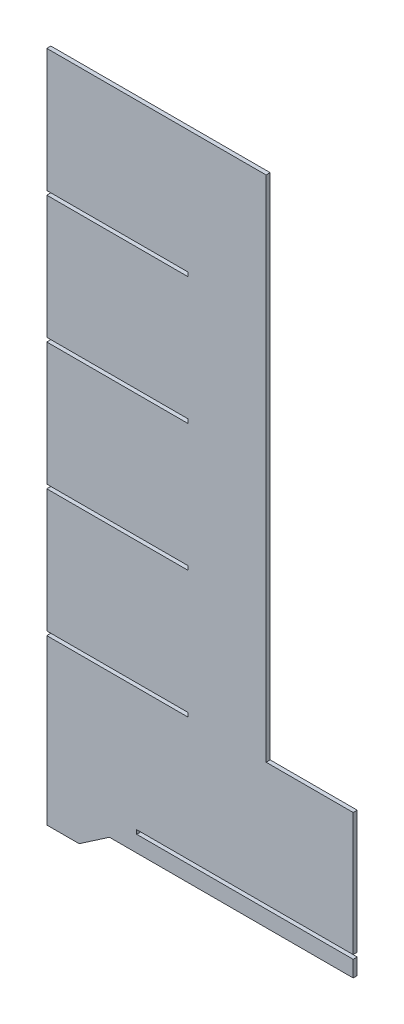
SolidWorks part; units mm, degrees
material "6061-T6 (SS)"
ref_plane "X-Y Datum" through (0, 0, 0) normal (0, 0, 1) x (1, 0, 0)
ref_plane "X-Z Datum" through (0, 0, 0) normal (0, 1, 0) x (1, 0, 0)
ref_plane "Y-Z Datum" through (0, 0, 0) normal (1, 0, 0) x (0, 0, -1)
sketch "Sketch1" plane through (0, 0, 0) normal (0, 0, 1) x (1, 0, 0)
  line L1 (129.0131, 254.2454) -> (-18.6854, 254.2454)
  line L3 (129.0131, -241.3467) -> (-18.6854, -241.3467)
  line L4 (-18.6854, 254.2454) -> (-18.6854, 157.667)
  line L24 (129.0131, 254.2454) -> (129.0131, -241.3467)
  line L25 (92.0885, 157.667) -> (-18.6854, 157.667)
  line L27 (92.0885, 154.492) -> (-18.6854, 154.492)
  line L29 (92.0885, 57.9136) -> (-18.6854, 57.9136)
  line L31 (92.0885, 54.7386) -> (-18.6854, 54.7386)
  line L33 (92.0885, -41.8399) -> (-18.6854, -41.8399)
  line L35 (92.0885, -45.0149) -> (-18.6854, -45.0149)
  line L37 (92.0885, -141.5933) -> (-18.6854, -141.5933)
  line L39 (92.0885, -144.7683) -> (-18.6854, -144.7683)
  line L41 (92.0885, -141.5933) -> (92.0885, -144.7683)
  line L42 (92.0885, -41.8399) -> (92.0885, -45.0149)
  line L43 (92.0885, 57.9136) -> (92.0885, 54.7386)
  line L44 (-18.6854, -144.7683) -> (-18.6854, -241.3467)
  line L45 (-18.6854, -45.0149) -> (-18.6854, -141.5933)
  line L46 (-18.6854, 54.7386) -> (-18.6854, -41.8399)
  line L47 (-18.6854, 154.492) -> (-18.6854, 57.9136)
  line L48 (92.0885, 157.667) -> (92.0885, 154.492)
extrude "Boss-Extrude2" add sketch "Sketch1" along normal blind 3.175
sketch "Sketch4" plane through (0, 0, 3.175) normal (0, 0, 1) x (1, 0, 0)
  line L1 (129.0131, 254.2454) -> (153.4072, 254.2454)
  line L2 (129.0131, 254.2454) -> (129.0131, -241.3467)
  line L3 (129.0131, -241.3467) -> (153.4072, -241.3467)
  line L4 (153.4072, 254.2454) -> (153.4072, -241.3467)
extrude "Boss-Extrude3" add sketch "Sketch4" against normal through all
sketch "Sketch6" plane through (0, 0, 3.175) normal (0, 0, 1) x (1, 0, 0)
  line L0 (-18.6854, -241.3467) -> (-18.6854, -355.6467)
  line L1 (-18.6854, -355.6467) -> (32.1146, -355.6467)
  line L3 (153.4072, -241.3467) -> (-18.6854, -241.3467)
  line L4 (153.4072, -241.3467) -> (153.4072, -292.1467)
  line L5 (153.4072, -292.1467) -> (32.1146, -355.6467)
extrude "Boss-Extrude5" [suppressed] add sketch "Sketch6" against normal through all
sketch "Sketch7" plane through (0, 0, 3.175) normal (0, 0, 1) x (1, 0, 0)
  line L0 (51.8072, -241.3467) -> (-18.6854, -241.3467)
  line L1 (51.8072, -244.5217) -> (51.8072, -241.3467)
  line L2 (153.4072, -244.5217) -> (51.8072, -244.5217)
  line L3 (153.4072, -244.5217) -> (153.4072, -257.2217)
  line L4 (153.4072, -257.2217) -> (30.4963, -257.2217)
  line L5 (30.4963, -257.2217) -> (6.7146, -273.4777)
  line L6 (-18.6854, -273.4777) -> (6.7146, -273.4777)
  line L7 (-18.6854, -241.3467) -> (-18.6854, -273.4777)
  point P0 (-51.634, -260.9767)
  point P9 (-18.6854, -241.3467)
extrude "Boss-Extrude6" add sketch "Sketch7" against normal through all
sketch "Sketch8" plane through (0, 0, 3.175) normal (0, 0, 1) x (1, 0, 0)
  line L1 (153.4072, -257.2217) -> (221.7231, -257.2217)
  line L2 (153.4072, -257.2217) -> (153.4072, -244.5217)
  line L3 (153.4072, -244.5217) -> (221.7231, -244.5217)
  line L4 (221.7231, -257.2217) -> (221.7231, -244.5217)
  line L5 (153.4072, -241.3467) -> (221.7231, -241.3467)
  line L6 (153.4072, -241.3467) -> (153.4072, -144.7683)
  line L7 (153.4072, -144.7683) -> (221.7231, -144.7683)
  line L8 (221.7231, -241.3467) -> (221.7231, -144.7683)
  dimension "D1" = 68.3158
extrude "Boss-Extrude7" add sketch "Sketch8" against normal through all
